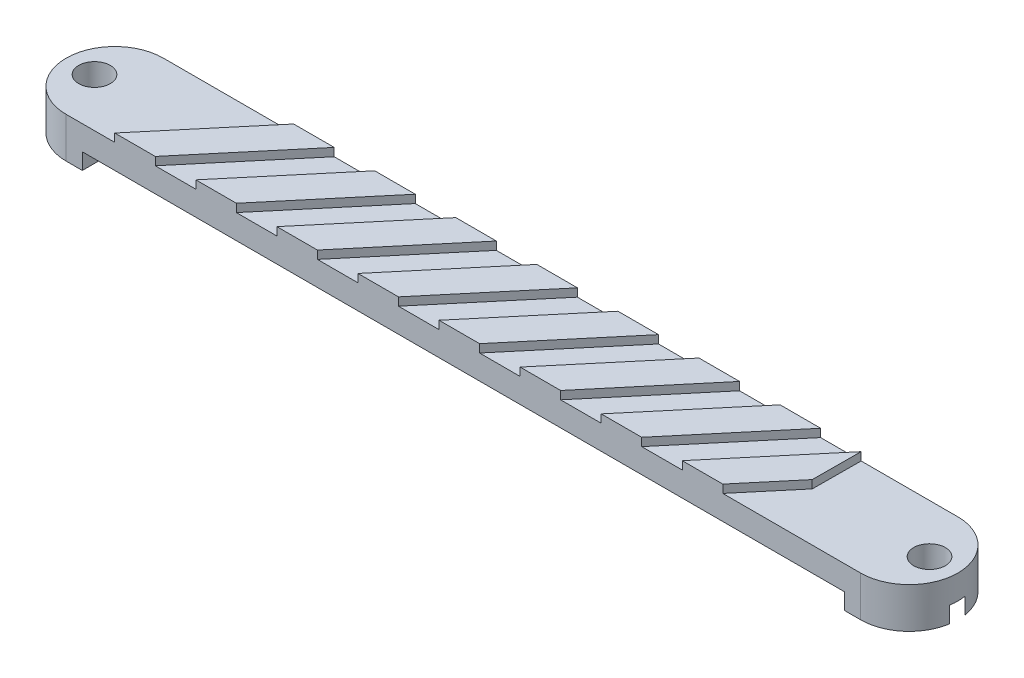
SolidWorks part; units mm, degrees
ref_plane "Front Plane" through (0, 0, 0) normal (0, 0, 1) x (1, 0, 0)
ref_plane "Top Plane" through (0, 0, 0) normal (0, 1, 0) x (1, 0, 0)
ref_plane "Right Plane" through (0, 0, 0) normal (1, 0, 0) x (0, 0, -1)
sketch "Sketch1" plane through (0, 0, 0) normal (0, 1, 0) x (1, 0, 0)
  line L0 (-49, 0) -> (49, 0) construction
  line L1 (-49, 6) -> (49, 6)
  line L2 (-49, -6) -> (49, -6)
  arc A0 (-49, 6) -> (-49, -6) centre (-49, 0) ccw
  arc A1 (49, -6) -> (49, 6) centre (49, 0) ccw
  circle A2 centre (-51.5, 0) radius 1.95
  circle A3 centre (51.5, 0) radius 1.95
  point P2 (0, 0)
  point P12 (-55, 0)
  point P13 (55, 0)
  dimension "D3" = 3.9
  dimension "D4" = 3.5
  dimension "D1" = 110
  dimension "D2" = 12
  dimension "D5" = 3.5
extrude "Boss-Extrude1" add sketch "Sketch1" along normal blind 3 contours L2 A1 L1 A0 | A2 | A3
sketch "Sketch2" plane through (0, 0, 0) normal (0, -1, 0) x (1, 0, 0)
  line L0 (-49, 6) -> (49, 6) construction
  line L1 (53.4919, -3.45) -> (55.4837, 0)
  line L2 (55.4837, 0) -> (53.4919, 3.45)
  line L3 (53.4919, 3.45) -> (49.5081, 3.45)
  line L4 (49.5081, 3.45) -> (47.5163, 0)
  line L5 (47.5163, 0) -> (49.5081, -3.45)
  line L6 (49.5081, -3.45) -> (53.4919, -3.45)
  line L7 (47, 6) -> (47, -6)
  line L8 (-49, -6) -> (49, -6) construction
  line L9 (47, -6) -> (49, -6)
  line L10 (49, 6) -> (47, 6)
  line L11 (0, 0) -> (0, -50000) construction
  line L12 (-49, 6) -> (-47, 6)
  line L13 (-47, -6) -> (-49, -6)
  line L14 (-47, 6) -> (-47, -6)
  line L15 (-49.5081, -3.45) -> (-53.4919, -3.45)
  line L16 (-47.5163, 0) -> (-49.5081, -3.45)
  line L17 (-49.5081, 3.45) -> (-47.5163, 0)
  line L18 (-53.4919, 3.45) -> (-49.5081, 3.45)
  line L19 (-55.4837, 0) -> (-53.4919, 3.45)
  line L20 (-53.4919, -3.45) -> (-55.4837, 0)
  circle A5 centre (51.5, 0) radius 1.95 construction
  circle A6 centre (51.5, 0) radius 1.95
  circle A7 centre (51.5, 0) radius 3.45 construction
  arc A8 (49, -6) -> (49, 6) centre (49, 0) ccw
  circle A9 centre (-51.5, 0) radius 3.45 construction
  arc A10 (-49, -6) -> (-49, 6) centre (-49, 0) cw
  circle A11 centre (-51.5, 0) radius 1.95
  arc M4 (-49, 6) -> (-49, -6) centre (-49, 0) ccw
  line M5 (-49, -6) -> (49, -6)
  arc M6 (49, -6) -> (49, 6) centre (49, 0) ccw
  line M7 (49, 6) -> (-49, 6)
  dimension "D1" = 6.9
  dimension "D3" = 2
extrude "Boss-Extrude2" add sketch "Sketch2" along normal blind 2 contours L7 L6 L5 L4 L3 L2 L1 M7 M5 M6 | L14 L15 L20 L19 L18 L17 L16 M7 M4 M5
sketch "Sketch3" plane through (0, 3, 0) normal (0, 1, 0) x (1, 0, 0)
  line L0 (-32.9308, 6) -> (-43, -6)
  line L1 (-49, 6) -> (49, 6) construction
  line L2 (-49, -6) -> (49, -6) construction
  line L3 (-43, -6) -> (-38, -6)
  line L4 (-38, -6) -> (-27.9308, 6)
  line L5 (-27.9308, 6) -> (-32.9308, 6)
  line L6 (-17.9308, 6) -> (-22.9308, 6)
  line L7 (-22.9308, 6) -> (-33, -6)
  line L8 (-33, -6) -> (-28, -6)
  line L9 (-28, -6) -> (-17.9308, 6)
  line L10 (-7.9308, 6) -> (-12.9308, 6)
  line L11 (-12.9308, 6) -> (-23, -6)
  line L12 (-23, -6) -> (-18, -6)
  line L13 (-18, -6) -> (-7.9308, 6)
  line L14 (2.0692, 6) -> (-2.9308, 6)
  line L15 (-2.9308, 6) -> (-13, -6)
  line L16 (-13, -6) -> (-8, -6)
  line L17 (-8, -6) -> (2.0692, 6)
  line L18 (12.0692, 6) -> (7.0692, 6)
  line L19 (7.0692, 6) -> (-3, -6)
  line L20 (-3, -6) -> (2, -6)
  line L21 (2, -6) -> (12.0692, 6)
  line L22 (22.0692, 6) -> (17.0692, 6)
  line L23 (17.0692, 6) -> (7, -6)
  line L24 (7, -6) -> (12, -6)
  line L25 (12, -6) -> (22.0692, 6)
  line L26 (32.0692, 6) -> (27.0692, 6)
  line L27 (27.0692, 6) -> (17, -6)
  line L28 (17, -6) -> (22, -6)
  line L29 (22, -6) -> (32.0692, 6)
  line L31 (37.0692, 6) -> (27, -6)
  line L32 (27, -6) -> (32, -6)
  line L33 (32, -6) -> (37.0346, 0)
  line L34 (37.0692, 6) -> (37.0346, 0)
  line L36 (42.0692, 6) -> (37.0692, 6) [skipped]
  arc A0 (-49, 6) -> (-49, -6) centre (-49, 0) ccw construction
  point P39 (-55, 0)
  dimension "D1" = 5
  dimension "D2" = 50
  dimension "D4" = 12
  dimension "D3" = 8
extrude "Boss-Extrude3" add sketch "Sketch3" along normal blind 1
